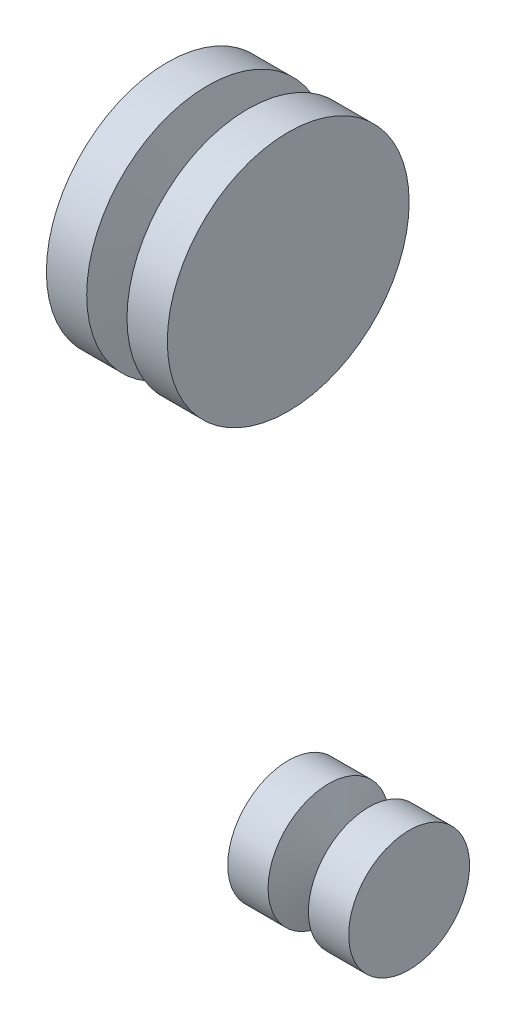
SolidWorks part; units mm, degrees
ref_plane "Front Plane" through (0, 0, 0) normal (0, 0, 1) x (1, 0, 0)
ref_plane "Top Plane" through (0, 0, 0) normal (0, 1, 0) x (1, 0, 0)
ref_plane "Right Plane" through (0, 0, 0) normal (1, 0, 0) x (0, 0, -1)
sketch "Sketch1" plane through (0, 0, 0) normal (1, 0, 0) x (0, 0, -1)
  circle A0 centre (-30, 150) radius 10
  circle A1 centre (-20, 100) radius 5
  point P4 (-15.0938, 49.384)
  point P5 (0, 0)
  point P6 (0, 0)
  point P7 (-18.8991, 118.6204)
  point P8 (-20.9025, 167.6878)
  point P10 (-30, 165.817)
  dimension "D1" = 10
  dimension "D4" = 20
  dimension "D2" = 50
  dimension "D3" = 10
  dimension "D5" = 20
  dimension "D6" = 100
extrude "Boss-Extrude1" add sketch "Sketch1" along normal mid plane 10
ref_plane "Plane2" through (0, 0, 30) normal (0, 0, 1) x (1, 0, 0)
ref_plane "Plane3" through (0, 0, 20) normal (0, 0, 1) x (1, 0, 0)
sketch "Sketch2" plane through (0, 0, 20) normal (0, 0, 1) x (1, 0, 0)
  line L0 (-5, 100) -> (5, 100) construction
  line L1 (-5, 105) -> (-5, 95) construction
  line L2 (5, 95) -> (5, 105) construction
  line L3 (0, 95) -> (0, 105) construction
  line L4 (5, 105) -> (-5, 105) construction
  line L6 (0.5, 101) -> (1.6667, 105)
  line L8 (5, 95) -> (5, 105)
  line L9 (-5, 105) -> (-5, 95)
  line L11 (-5, 95) -> (5, 95) construction
  line L12 (-1.6667, 105) -> (1.6667, 105)
  line L13 (-1.6667, 105) -> (-0.5, 101)
  line L14 (0.5, 101) -> (-0.5, 101)
  point P15 (0, 101)
  point P18 (1.6667, 105)
  point P19 (0, 0)
  point P20 (0, 0)
  point P21 (1.6667, 105)
  dimension "D1" = 3.3333
  dimension "D2" = 3.3333
  dimension "D3" = 1
  dimension "D4" = 1
  dimension "D5" = 1.6667
revolve "Cut-Revolve3" cut sketch "Sketch2" angle 360 about L0
sketch "Sketch3" plane through (0, 0, 30) normal (0, 0, 1) x (1, 0, 0)
  line L0 (0, 160) -> (0, 140) construction
  line L1 (5, 160) -> (-5, 160) construction
  line L2 (-5, 140) -> (5, 140) construction
  line L3 (-5, 150) -> (5, 150) construction
  line L4 (-5, 160) -> (-5, 140) construction
  line L5 (5, 140) -> (5, 160) construction
  line L6 (1.6667, 160) -> (-1.6667, 160)
  line L7 (1.6667, 160) -> (0.5, 151)
  line L8 (-1.6667, 160) -> (-0.5, 151)
  line L9 (-0.5, 151) -> (0.5, 151)
  point P16 (0, 151)
  point P17 (1.6667, 160)
  point P18 (1.6667, 160)
  point P21 (-1.6667, 160)
  dimension "D1" = 1
  dimension "D2" = 3.3333
  dimension "D3" = 3.3333
  dimension "D4" = 1
revolve "Cut-Revolve4" cut sketch "Sketch3" angle 360 about L3
